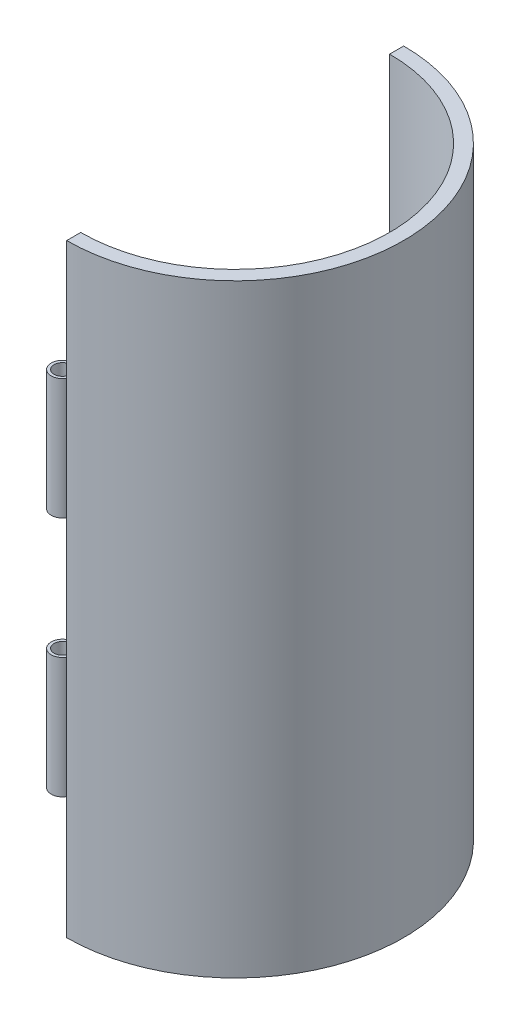
SolidWorks part; units mm, degrees
ref_plane "Front Plane" through (0, 0, 0) normal (0, 0, 1) x (1, 0, 0)
ref_plane "Top Plane" through (0, 0, 0) normal (0, 1, 0) x (1, 0, 0)
ref_plane "Right Plane" through (0, 0, 0) normal (1, 0, 0) x (0, 0, -1)
sketch "Sketch1" plane through (0, 0, 0) normal (0, 1, 0) x (1, 0, 0)
  line L0 (0, 30) -> (0, -30)
  line L1 (0, -30) -> (0, -27.5) construction
  circle A0 centre (0, 0) radius 30
  circle A1 centre (0, 0) radius 27.5
  dimension "D1" = 60
  dimension "D2" = 2.5
extrude "Boss-Extrude1" add sketch "Sketch1" along normal blind 107.5 contours A1 L0 A0
sketch "Sketch2" plane through (0, 0, 0) normal (0, -1, 0) x (1, 0, 0)
  line L0 (0, 28.75) -> (-2, 28.75) construction
  line L1 (0, 27.5) -> (0, 30) construction
  circle A0 centre (-2, 28.75) radius 2
  circle A1 centre (-2, 28.75) radius 1.5
  dimension "D1" = 2
  dimension "D2" = 0.5
extrude "Boss-Extrude2" add sketch "Sketch2" against normal blind 21.5 from offset 21.5 separate body offset against normal yes
sketch "Sketch3" plane through (0, 0, 0) normal (-1, 0, 0) x (0, 0, 1)
  line L0 (28.75, 107.5) -> (28.75, 0) construction
  line L1 (27.5, 107.5) -> (30, 107.5) construction
pattern_linear "LPattern1" count 2 spacing 43 along (0, 1, 0) of "Boss-Extrude2"
